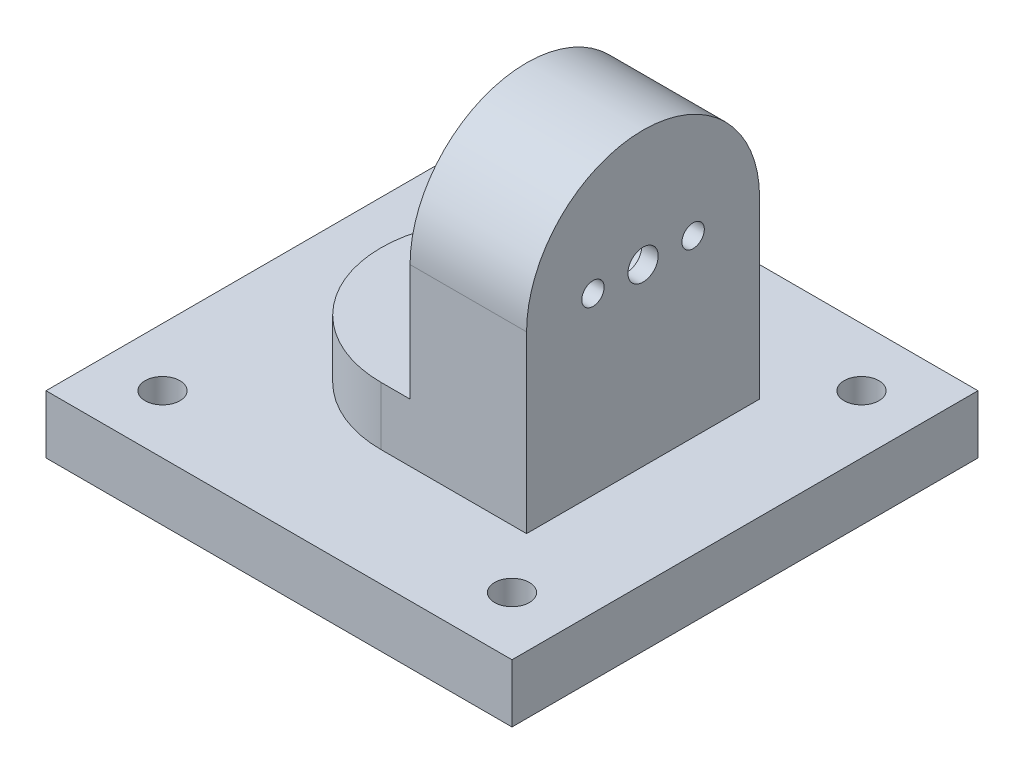
SolidWorks part; units mm, degrees
ref_plane "Front Plane" through (0, 0, 0) normal (0, 0, 1) x (1, 0, 0)
ref_plane "Top Plane" through (0, 0, 0) normal (0, 1, 0) x (1, 0, 0)
ref_plane "Right Plane" through (0, 0, 0) normal (1, 0, 0) x (0, 0, -1)
sketch "Sketch1" plane through (0, 0, 0) normal (0, 1, 0) x (1, 0, 0)
  circle A0 centre (0, 0) radius 12.7
  dimension "D1" = 25.4
extrude "Boss-Extrude1" add sketch "Sketch1" along normal blind 6.35
sketch "Sketch14" plane through (0, 6.35, 0) normal (0, 1, 0) x (1, 0, 0)
  line L0 (0, 12.7) -> (15.875, 12.7)
  line L1 (15.875, 12.7) -> (15.875, -12.7)
  line L2 (15.875, -12.7) -> (0, -12.7)
  circle A0 centre (0, 0) radius 12.7
  circle M3 centre (0, 0) radius 12.7
  dimension "D1" = 25.4
  dimension "D2" = 15.875
extrude "Boss-Extrude6" add sketch "Sketch14" against normal up to surface (6.35 mm away) contours L2 L1 L0 M3 up to face at (0, 0, 12.7)
sketch "Sketch15" plane through (15.875, 0, 0) normal (1, 0, 0) x (0, 0, -1)
  line L1 (12.7, 6.35) -> (-12.7, 6.35) construction
  line L2 (-12.7, 19.05) -> (-12.7, 6.35)
  line L3 (-12.7, 6.35) -> (12.7, 6.35)
  line L4 (12.7, 6.35) -> (12.7, 19.05)
  circle A0 centre (0, 19.05) radius 12.7
  line M4 (12.7, 6.35) -> (-12.7, 6.35)
  dimension "D1" = 25.4
  dimension "D2" = 12.7
  dimension "D3" = 0
extrude "Boss-Extrude8" add sketch "Sketch15" against normal blind 12.7 contours A0 | A0 L2 L3 | A0 L4 M4
sketch "Sketch17" plane through (3.175, 0, 0) normal (-1, 0, 0) x (0, 0, 1)
  line L0 (-12.7, 19.05) -> (12.7, 19.05) construction
  line L1 (0, 31.75) -> (0, 6.35) construction
  line L2 (-12.7, 6.35) -> (12.7, 6.35) construction
  arc A0 (12.7, 19.05) -> (-12.7, 19.05) centre (0, 19.05) ccw construction
  circle A1 centre (0, 19.05) radius 1.651
  dimension "D1" = 3.302
extrude "Cut-Extrude4" cut sketch "Sketch17" against normal up to surface (12.7 mm away) up to face at (15.875, 12.7, 0)
sketch "Sketch18" plane through (3.175, 0, 0) normal (-1, 0, 0) x (0, 0, 1)
  circle A0 centre (0, 19.05) radius 3.81
  dimension "D1" = 7.62
extrude "Cut-Extrude5" cut sketch "Sketch18" against normal offset from surface (10.9028 mm away) 1.7972 up to face at (15.875, 19.05, 1.651)
sketch "Sketch19" plane through (3.175, 0, 0) normal (-1, 0, 0) x (0, 0, 1)
  circle A0 centre (0, 19.05) radius 8.255
  dimension "D1" = 16.51
extrude "Cut-Extrude6" cut sketch "Sketch19" against normal offset from surface (8.3628 mm away) 4.3372 up to face at (15.875, 19.05, 1.651)
sketch "Sketch20" plane through (3.175, 0, 0) normal (-1, 0, 0) x (0, 0, 1)
  circle A0 centre (0, 19.05) radius 9.525
  dimension "D1" = 19.05
extrude "Cut-Extrude7" cut sketch "Sketch20" against normal offset from surface (5.1878 mm away) 7.5122 up to face at (15.875, 19.05, 1.651)
sketch "Sketch21" plane through (11.5378, 0, 0) normal (-1, 0, 0) x (0, 0, 1)
  line L0 (8.255, 19.05) -> (-8.255, 19.05) construction
  circle A0 centre (0, 19.05) radius 8.255 construction
  circle A1 centre (5.46, 19.05) radius 1.2192
  circle A2 centre (-5.46, 19.05) radius 1.2192
  circle A3 centre (0, 19.05) radius 1.651 construction
  dimension "D1" = 2.4384
  dimension "D2" = 2.4384
  dimension "D3" = 10.92
  dimension "D4" = 5.46
extrude "Cut-Extrude8" cut sketch "Sketch21" against normal up to surface (4.3372 mm away) up to face at (15.875, 19.05, 1.651)
sketch "Sketch22" plane through (0, 0, 0) normal (0, -1, 0) x (1, 0, 0)
  line L0 (15.875, 12.7) -> (15.875, -12.7) construction
  line L1 (26.9875, 25.4) -> (-23.8125, 25.4)
  line L2 (26.9875, 25.4) -> (26.9875, -25.4)
  line L3 (26.9875, -25.4) -> (-23.8125, -25.4)
  line L4 (-23.8125, 25.4) -> (-23.8125, -25.4)
  line L5 (26.9875, 25.4) -> (-23.8125, -25.4) construction
  line L6 (26.9875, -25.4) -> (-23.8125, 25.4) construction
  point P0 (1.5875, 0)
  point P6 (15.875, 0)
  dimension "D1" = 14.2875
  dimension "D2" = 50.8
  dimension "D3" = 50.8
  dimension "D4" = 0
extrude "Boss-Extrude9" add sketch "Sketch22" along normal blind 6.35
hole_wizard "#6 Clearance Hole1" positions "Sketch24" profile "Sketch25" hole size "#6" standard "ANSI Inch"
sketch "Sketch24" plane through (0, -6.35, 0) normal (0, -1, 0) x (-1, 0, 0)
  line L0 (23.8125, 25.4) -> (-26.9875, 25.4) construction
  line L1 (-26.9875, 25.4) -> (-26.9875, -25.4) construction
  line L2 (23.8125, -25.4) -> (23.8125, 25.4) construction
  line L3 (-26.9875, -25.4) -> (23.8125, -25.4) construction
  point P0 (-20.6375, 19.05)
  point P2 (17.4625, 19.05)
  point P4 (17.4625, -19.05)
  point P6 (-20.6375, -19.05)
  dimension "D1" = 6.35
  dimension "D2" = 6.35
  dimension "D3" = 6.35
  dimension "D4" = 6.35
  dimension "D5" = 6.35
  dimension "D6" = 6.35
  dimension "D7" = 6.35
  dimension "D8" = 6.35
sketch "Sketch25" plane through (20.6375, -6.35, -19.05) normal (1, 0, 0) x (0, 0, -1)
  line L0 (0, 0) -> (0, 26.5408)
  line L1 (0, 26.5408) -> (1.8986, 25.4)
  line L2 (1.8986, 25.4) -> (1.8986, 0)
  line L5 (1.8986, 0) -> (0, 0)
  line L10 (0, 26.5408) -> (-1.8986, 25.4) construction
  line L11 (0, -6.35) -> (0, 107.95) construction
  dimension "Hole Dia." = 3.7973
  dimension "Hole Depth" = 25.4
  dimension "Drill Angle" = 118
